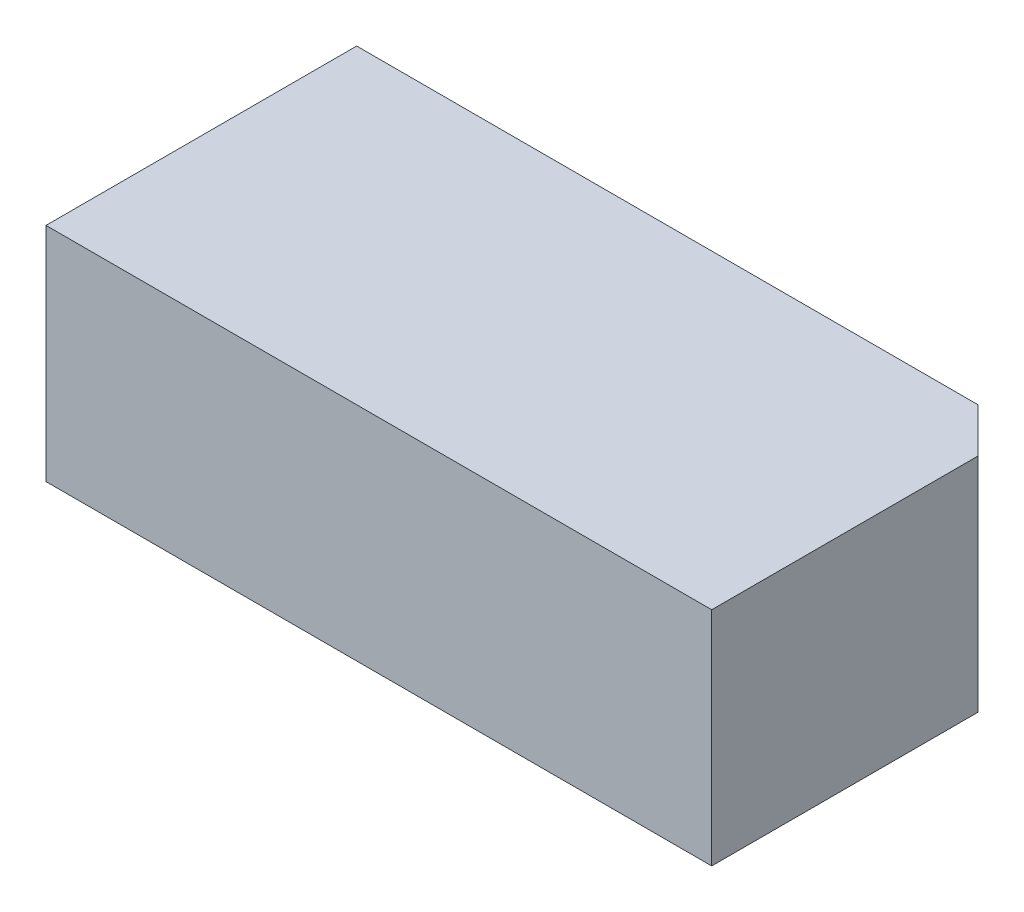
SolidWorks part; units mm, degrees
ref_plane "前视基准面" through (0, 0, 0) normal (0, 0, 1) x (1, 0, 0)
ref_plane "上视基准面" through (0, 0, 0) normal (0, 1, 0) x (1, 0, 0)
ref_plane "右视基准面" through (0, 0, 0) normal (1, 0, 0) x (0, 0, -1)
sketch "草图1" plane through (0, 0, 0) normal (0, 0, 1) x (1, 0, 0)
  line L1 (-13.477, 3.0172) -> (1.523, 3.0172)
  line L2 (-13.477, 3.0172) -> (-13.477, -1.9828)
  line L3 (-13.477, -1.9828) -> (1.523, -1.9828)
  line L4 (1.523, 3.0172) -> (1.523, -1.9828)
  line L5 (-13.477, 3.0172) -> (1.523, -1.9828) construction
  line L6 (-13.477, -1.9828) -> (1.523, 3.0172) construction
  point P0 (-5.977, 0.5172)
  dimension "D1" = 15
  dimension "D2" = 5
extrude "凸台-拉伸1" add sketch "草图1" along normal blind 7
chamfer "倒角1" distance 1 angle 45 1 edges at (1.523, 0.5172, 0)
